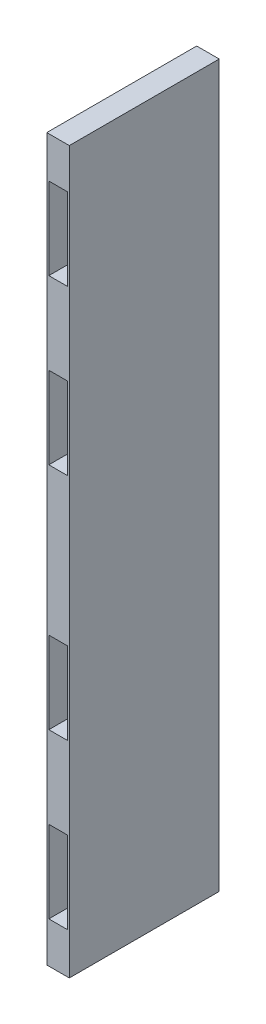
SolidWorks part; units mm, degrees
ref_plane "Top" through (0, 0, 0) normal (0, 0, 1) x (1, 0, 0)
ref_plane "Front" through (0, 0, 0) normal (0, 1, 0) x (1, 0, 0)
ref_plane "Right" through (0, 0, 0) normal (1, 0, 0) x (0, 0, -1)
sketch "Profile Sketch" plane through (0.0456, 0, -0.0242) normal (0, 1, 0) x (-1, 0, 0)
  line L0 (2.5456, -18.2758) -> (2.5456, 0.0242)
  line L1 (2.5456, 0.0242) -> (0.0456, 0.0242)
  line L2 (0.0456, 0.0242) -> (0.0456, -18.2758)
  line L3 (0.0456, -18.2758) -> (2.5456, -18.2758)
  line L12 (2.2956, 0.0242) -> (2.2956, -18.2758) construction
  dimension "D1" = 18.3
  dimension "D3" = 2.25
extrude "Profile Extrude" add sketch "Profile Sketch" along normal blind 88
ref_plane "Mid Plane" through (0, 44, 0) normal (0, -1, 0) x (-1, 0, 0)
ref_plane "Right Cut Out Location" through (0, 20, 0) normal (0, -1, 0) x (-1, 0, 0)
ref_plane "Left Cut Out Location" through (0, 68, 0) normal (0, -1, 0) x (-1, 0, 0)
sketch "Cover Latch Cut Out Sketch" plane through (-2.5, 0, 0) normal (-1, 0, 0) x (0, 0, 1)
  line L4 (-18.3, 27) -> (-18.3, 13)
  line L5 (0, 15) -> (-2.2, 15)
  line L10 (0, 25) -> (0, 15) construction
  line L11 (0, 88) -> (0, 0) construction
  line L12 (-2.2, 15) -> (-2.8583, 20)
  line L13 (-2.8583, 20) -> (-2.2, 25)
  line L14 (-2.2, 25) -> (0, 25)
  line L15 (-2.8583, 20) -> (0, 20) construction
  line L16 (0, 25) -> (0, 35)
  line L17 (0, 35) -> (-8.8583, 35)
  line L18 (0, 15) -> (0, 5)
  line L21 (0, 5) -> (-8.8583, 5)
  line L22 (-8.8583, 35) -> (-8.8583, 27)
  line L23 (-8.8583, 27) -> (-18.3, 27)
  line L24 (-8.8583, 5) -> (-8.8583, 13)
  line L25 (-8.8583, 13) -> (-18.3, 13)
  line L27 (-18.3, 88) -> (-18.3, 0) construction
  point P3 (0, 44)
  dimension "D2" = 10
  dimension "D3" = 10
  dimension "D4" = 7.5
  dimension "Latch Depth" = 2.2
  dimension "D5" = 6
extrude "Cover Latch Cut Out" cut sketch "Cover Latch Cut Out Sketch" against normal blind 2.25
mirror "Cover Latch Cut Out Mirror" about plane through (0, 44, 0) normal (0, -1, 0) of "Cover Latch Cut Out"
sketch "Side Sketch" plane through (0, 0, 0) normal (0, 1, 0) x (1, 0, 0)
  line L7 (-2.75, 18.3) -> (-2.5, 18.3)
  line L8 (-2.75, 18.3) -> (-2.75, 0)
  line L9 (-2.75, 0) -> (-2.5, 0)
  line L10 (-2.5, 18.3) -> (-2.5, 0)
extrude "Side Extrude" add sketch "Side Sketch" along normal through all
